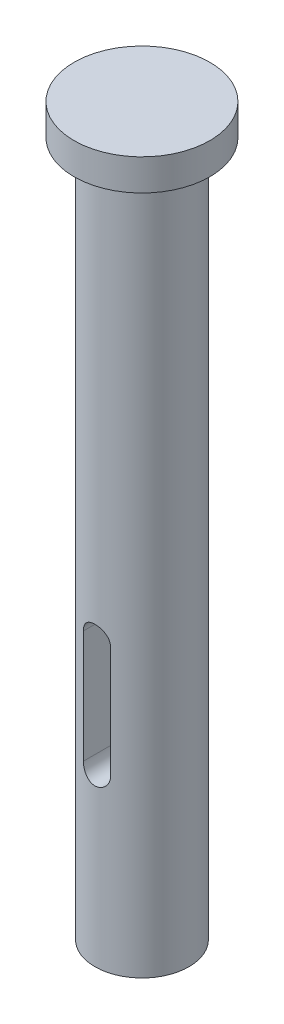
SolidWorks part; units mm, degrees
material "PVC Rigid"
ref_plane "Front Plane" through (0, 0, 0) normal (0, 0, 1) x (1, 0, 0)
ref_plane "Top Plane" through (0, 0, 0) normal (0, 1, 0) x (1, 0, 0)
ref_plane "Right Plane" through (0, 0, 0) normal (1, 0, 0) x (0, 0, -1)
sketch "Sketch1" plane through (0, 0, 0) normal (0, 1, 0) x (1, 0, 0)
  circle A0 centre (0, 0) radius 11.43
  dimension "D1" = 22.86
extrude "Boss-Extrude1" add sketch "Sketch1" along normal blind 176.53
ref_plane "Plane1" through (0, 0, 11.43) normal (0, 0, 1) x (1, 0, 0)
sketch "Sketch2" plane through (0, 0, 11.43) normal (0, 0, 1) x (1, 0, 0)
  line L0 (0, 0) -> (0, 38.1) construction
  line L1 (0, 176.53) -> (0, 72.136) construction
  line L2 (11.43, 176.53) -> (-11.43, 176.53) construction
  line L5 (3.302, 41.402) -> (3.302, 68.834)
  line L7 (-3.302, 41.402) -> (-3.302, 68.834)
  arc A0 (-3.302, 68.834) -> (3.302, 68.834) centre (0, 68.834) cw
  arc A1 (-3.302, 41.402) -> (3.302, 41.402) centre (0, 41.402) ccw
  point P11 (0, 72.136)
  point P18 (0, 38.1)
  dimension "D4" = 3.302
  dimension "D5" = 3.302
  dimension "D1" = 38.1
  dimension "D2" = 34.036
  dimension "D3" = 6.604
extrude "Cut-Extrude1" cut sketch "Sketch2" against normal blind 73.66
sketch "Sketch3" plane through (0, 176.53, 0) normal (0, 1, 0) x (1, 0, 0)
  circle A0 centre (0, 0) radius 16.51
  circle A1 centre (0, 0) radius 11.43
  dimension "D1" = 33.02
extrude "Boss-Extrude2" add sketch "Sketch3" against normal blind 7.62
